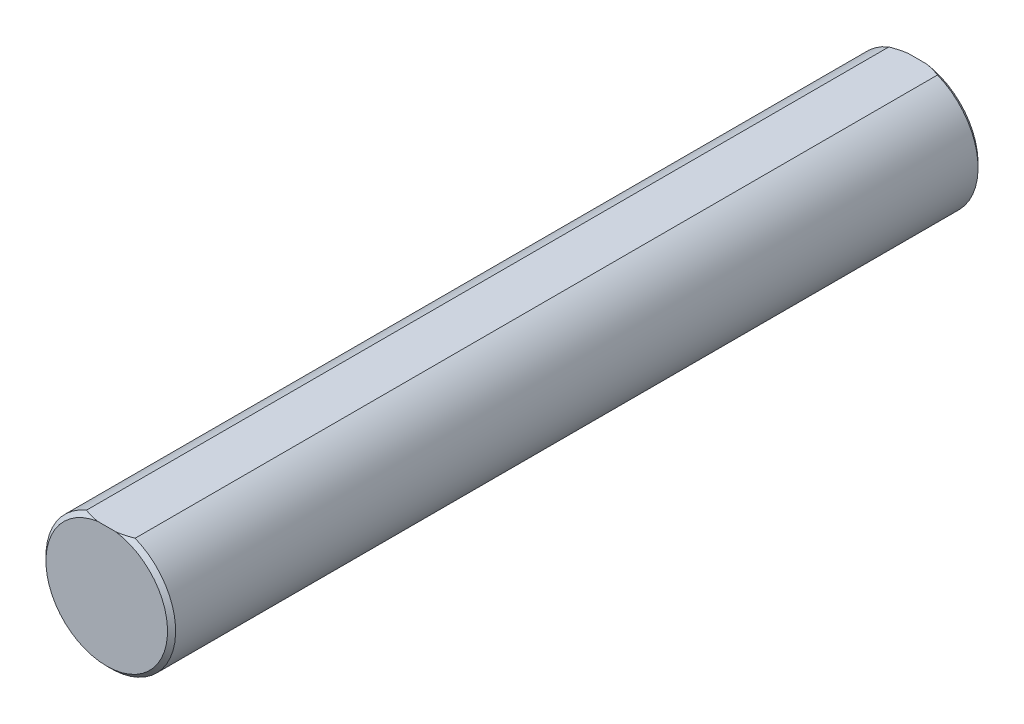
SolidWorks part; units mm, degrees
ref_plane "Front Plane" through (0, 0, 0) normal (0, 0, 1) x (1, 0, 0)
ref_plane "Top Plane" through (0, 0, 0) normal (0, 1, 0) x (1, 0, 0)
ref_plane "Right Plane" through (0, 0, 0) normal (1, 0, 0) x (0, 0, -1)
sketch "Sketch1" plane through (0, 0, 0) normal (0, 0, 1) x (1, 0, 0)
  circle A0 centre (0, 0) radius 4
  dimension "D1" = 8
extrude "Boss-Extrude1" add sketch "Sketch1" along normal blind 50
sketch "Sketch2" plane through (0, 0, 50) normal (0, 0, 1) x (1, 0, 0)
  line L1 (-1, 3) -> (1, 3)
  line L2 (-1, 3) -> (-1, 5)
  line L3 (-1, 5) -> (1, 5)
  line L4 (1, 3) -> (1, 5)
  line L5 (-1, 3) -> (1, 5) construction
  line L6 (-1, 5) -> (1, 3) construction
  point P0 (0, 4)
  dimension "D1" = 2
  dimension "D2" = 4
extrude "Cut-Extrude1" [suppressed] cut sketch "Sketch2" against normal blind 50
chamfer "Chamfer1" distance 0.25 angle 45 1 edges at (4, 0, 50)
chamfer "Chamfer2" distance 0.25 angle 45 1 edges at (4, 0, 0)
sketch "Sketch4" plane through (0, 0, 50) normal (0, 0, 1) x (1, 0, 0)
  line L0 (1.5, 3.7081) -> (-1.5, 3.7081)
  circle A0 centre (0, 0) radius 4
  circle A1 centre (0, 0) radius 4 construction
  circle A2 centre (0, 0) radius 4 construction
  dimension "D1" = 3
extrude "Cut-Extrude2" cut sketch "Sketch4" against normal through all
